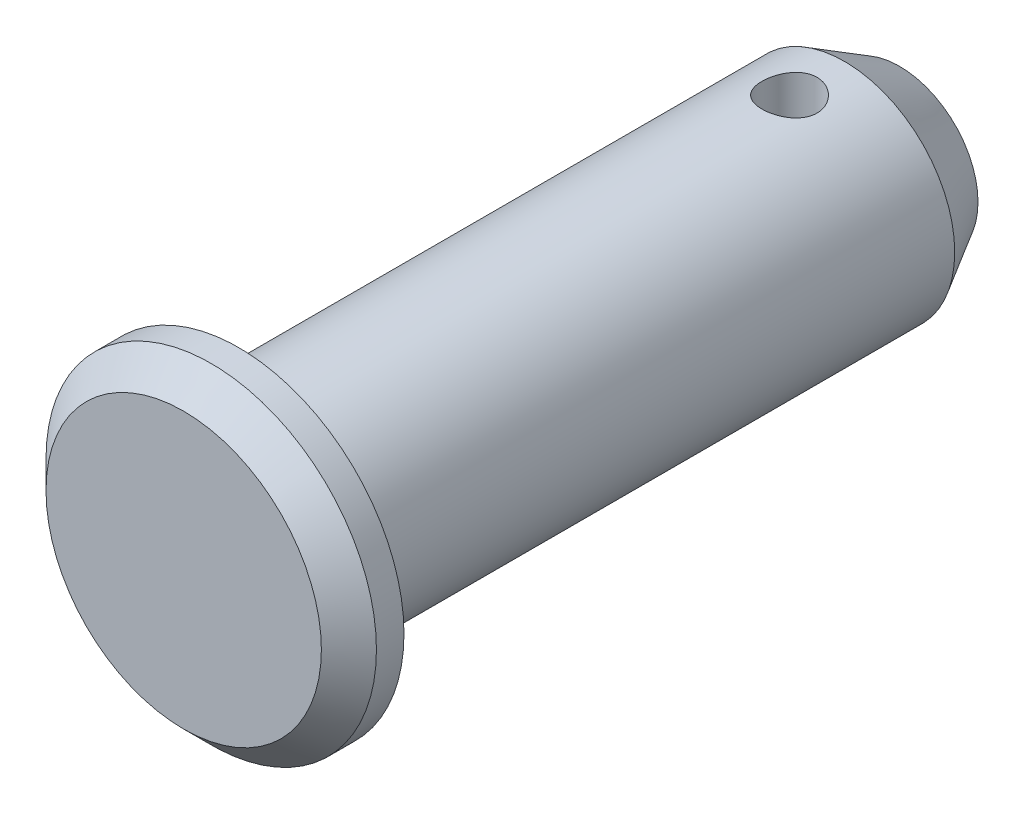
SolidWorks part; units mm, degrees
material "1.0545 (S355N)"
ref_plane "Płaszczyzna przednia" through (0, 0, 0) normal (0, 0, 1) x (1, 0, 0)
ref_plane "Płaszczyzna górna" through (0, 0, 0) normal (0, 1, 0) x (1, 0, 0)
ref_plane "Płaszczyzna prawa" through (0, 0, 0) normal (1, 0, 0) x (0, 0, -1)
sketch "Szkic1" plane through (0, 0, 0) normal (0, 1, 0) x (1, 0, 0)
  line L0 (2.5, -6.5) -> (-2.5, -6.5)
  line L1 (-3, -6) -> (-3, -5.5)
  line L2 (-3, -5.5) -> (-2, -5.5)
  line L3 (-2, -5.5) -> (-2, 5.5)
  line L4 (-1.4226, 6.5) -> (1.4226, 6.5)
  line L5 (2, 5.5) -> (2, -5.5)
  line L6 (2, -5.5) -> (3, -5.5)
  line L7 (3, -5.5) -> (3, -6)
  line L8 (3, -6) -> (2.5, -6.5)
  line L9 (-2.5, -6.5) -> (-3, -6)
  line L10 (1.4226, 6.5) -> (2, 5.5)
  line L11 (-2, 5.5) -> (-1.4226, 6.5)
  line L12 (0, -6.5) -> (0, 6.5)
  point P0 (3, -6.5)
  point P1 (-3, -6.5)
  point P5 (-2, 6.5)
  point P6 (2, 6.5)
  point P7 (0, 0)
  point P17 (0, 6.5)
  point P19 (0, -6.5)
  dimension "D1" = 6
  dimension "D2" = 4
  dimension "D3" = 1
  dimension "D4" = 30
  dimension "D8" = 30
  dimension "D9" = 12
  dimension "D10" = 1
revolve "Obrót1" add sketch "Szkic1" angle 360 about L12
sketch "Szkic2" plane through (0, 0, 0) normal (0, 1, 0) x (1, 0, 0)
  line L0 (2, -5.5) -> (-2, -5.5) construction
  circle A0 centre (0, 4.5) radius 0.5
  dimension "D2" = 1
  dimension "D1" = 10
extrude "Wytnij-wyciągnięcie1" cut sketch "Szkic2" against normal through all both and the other way through all contours A0
